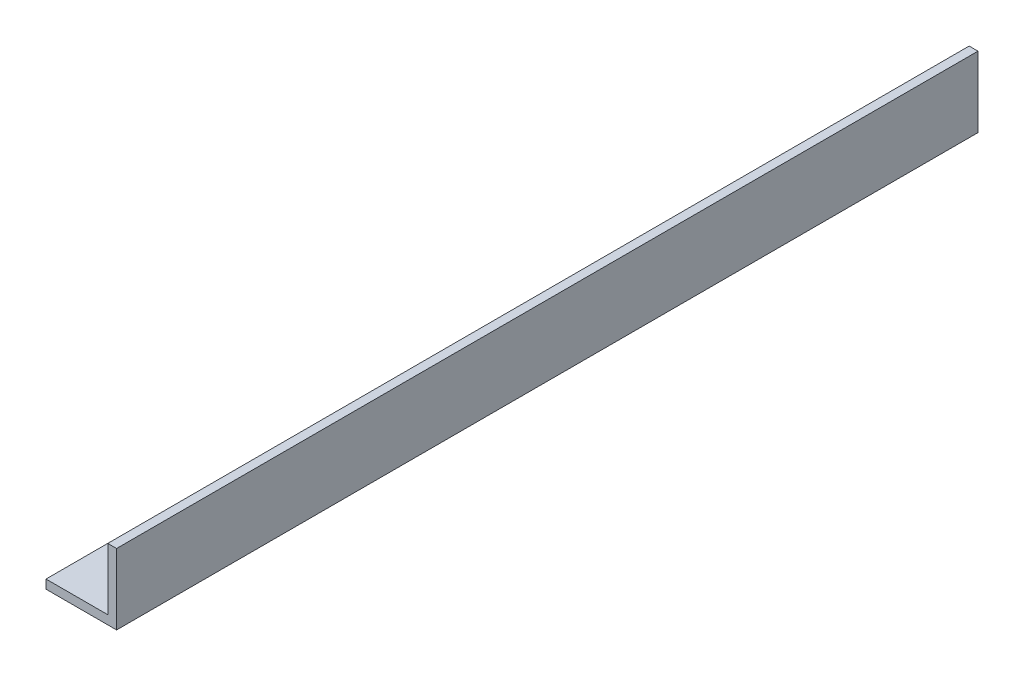
SolidWorks part; units mm, degrees
ref_plane "Front Plane" through (0, 0, 0) normal (0, 0, 1) x (1, 0, 0)
ref_plane "Top Plane" through (0, 0, 0) normal (0, 1, 0) x (1, 0, 0)
ref_plane "Right Plane" through (0, 0, 0) normal (1, 0, 0) x (0, 0, -1)
sketch "Sketch1" plane through (0, 0, 0) normal (0, 0, 1) x (1, 0, 0)
  line L0 (0, 0) -> (25.4, 0)
  line L1 (25.4, 0) -> (25.4, 25.4)
  line L2 (0, 3.175) -> (22.225, 3.175)
  line L3 (22.225, 3.175) -> (22.225, 25.4)
  line L4 (25.4, 25.4) -> (22.225, 25.4)
  line L5 (0, 3.175) -> (0, 0)
  dimension "D1" = 25.4
  dimension "D2" = 25.4
  dimension "D3" = 3.175
extrude "Boss-Extrude1" add sketch "Sketch1" along normal blind 310
sketch "Sketch2" plane through (0, 0, 0) normal (0, -1, 0) x (1, 0, 0)
  line L0 (0, 310) -> (25.4, 310) construction
  line L1 (25.4, 155) -> (0, 155) construction
  line L2 (25.4, 310) -> (25.4, 0) construction
  line L3 (0, 310) -> (0, 0) construction
  circle A0 centre (12.7, 290) radius 2
  circle A1 centre (12.7, 20) radius 2
  dimension "D1" = 20
extrude "Cut-Extrude1" cut sketch "Sketch2" against normal blind 310
